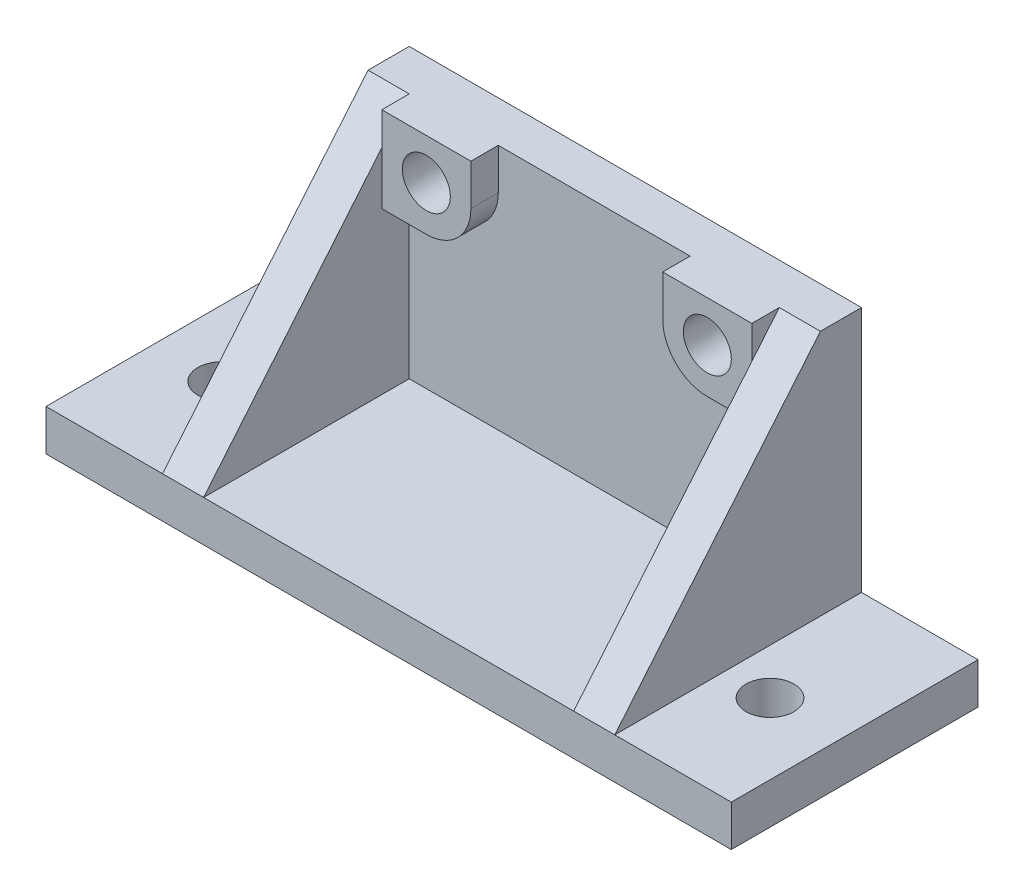
SolidWorks part; units mm, degrees
ref_plane "Alzado" through (0, 0, 0) normal (0, 0, 1) x (1, 0, 0)
ref_plane "Planta" through (0, 0, 0) normal (0, 1, 0) x (1, 0, 0)
ref_plane "Vista lateral" through (0, 0, 0) normal (1, 0, 0) x (0, 0, -1)
sketch "Croquis1" plane through (0, 0, 0) normal (0, 0, 1) x (1, 0, 0)
  point P0 (0, 0)
  point P8 (16.5, 0)
  line B0 (0, 0) -> (33, 0)
  line B1 (0, 0) -> (0, -21)
  line B2 (0, -21) -> (33, -21)
  line B3 (33, 0) -> (33, -21)
  circle B4 centre (6.25, -3) radius 1.75
  circle B5 centre (26.75, -3) radius 1.75
sketch_block_instance "Bloque1-1"
sketch_block "Bloque1"
extrude "Saliente-Extruir1" add sketch "Croquis1" along normal blind 3
sketch "Croquis2" plane through (0, 0, 3) normal (0, 0, 1) x (1, 0, 0)
  line L0 (0, 0) -> (0, -21)
  line L1 (0, -21) -> (33, -21)
  line L2 (33, -21) -> (33, 0)
  line L3 (33, 0) -> (30, 0)
  line L4 (33, 0) -> (0, 0) construction
  line L5 (30, 0) -> (30, -18)
  line L6 (30, -18) -> (3, -18)
  line L7 (3, -18) -> (3, 0)
  line L8 (3, 0) -> (0, 0)
  dimension "D1" = 3
  dimension "D2" = 3
  dimension "D3" = 3
extrude "Saliente-Extruir2" add sketch "Croquis2" along normal blind 15
sketch "Croquis3" plane through (0, 0, 0) normal (-1, 0, 0) x (0, 0, 1)
  line L0 (3, 0) -> (18, -18)
  line L1 (18, 0) -> (0, 0) construction
  line L2 (18, 0) -> (18, -21) construction
  line L3 (18, -18) -> (18, 0)
  line L4 (18, 0) -> (3, 0)
  line L5 (18, -21) -> (0, -21) construction
  dimension "D1" = 3
  dimension "D2" = 3
extrude "Cortar-Extruir1" cut sketch "Croquis3" against normal through all
sketch "Croquis4" plane through (0, -18, 0) normal (0, 1, 0) x (1, 0, 0)
  line L0 (30, -18) -> (3, -18) construction
  line L1 (0, -18) -> (-8.5, -18)
  line L2 (0, -18) -> (0, 0)
  line L3 (0, 0) -> (-8.5, 0)
  line L4 (-8.5, -18) -> (-8.5, 0)
  line L5 (33, 0) -> (41.5, 0)
  line L6 (33, 0) -> (33, -18)
  line L7 (33, -18) -> (41.5, -18)
  line L8 (41.5, 0) -> (41.5, -18)
  line L10 (33, 0) -> (0, 0) construction
  line L11 (33, -3) -> (33, -18) construction
  point P14 (55.1891, 0)
  dimension "D1" = 8.5
  dimension "D2" = 8.5
extrude "Saliente-Extruir3" add sketch "Croquis4" against normal up to surface (3 mm away) up to face at (16.5, -21, 9)
sketch "Croquis5" plane through (0, 0, 3) normal (0, 0, 1) x (1, 0, 0)
  line L0 (3, -18) -> (3, 0) construction
  line L1 (6.25, -6.25) -> (3, -6.25)
  line L2 (3, -6.25) -> (3, 0)
  line L3 (3, 0) -> (9.5, 0)
  line L4 (30, 0) -> (3, 0) construction
  line L5 (9.5, 0) -> (9.5, -3)
  line L6 (16.5, 0) -> (16.5, -18) construction
  line L7 (30, -18) -> (3, -18) construction
  line L8 (23.5, 0) -> (23.5, -3)
  line L9 (30, 0) -> (23.5, 0)
  line L10 (30, -6.25) -> (30, 0)
  line L11 (26.75, -6.25) -> (30, -6.25)
  arc A0 (6.25, -6.25) -> (9.5, -3) centre (6.25, -3) ccw
  arc A2 (26.75, -6.25) -> (23.5, -3) centre (26.75, -3) cw
  circle A3 centre (26.75, -3) radius 1.75 construction
  circle A4 centre (6.25, -3) radius 1.75 construction
  circle A5 centre (26.75, -3) radius 1.75
  circle A6 centre (6.25, -3) radius 1.75
extrude "Saliente-Extruir4" add sketch "Croquis5" along normal blind 2
sketch "Croquis6" plane through (33, 0, 0) normal (1, 0, 0) x (0, 0, -1)
  line L3 (-5, 0) -> (-5, -2.4)
  line L4 (-5, -2.4) -> (-3, 0)
  line L5 (-3, 0) -> (-5, 0)
  line L6 (-5, 0) -> (-5, -2.4)
  line L7 (-5, -2.4) -> (-3, 0)
  line L8 (-3, 0) -> (-5, 0)
  dimension "D1" = 0
sketch "Croquis8" plane through (0, -21, 0) normal (0, -1, 0) x (1, 0, 0)
  circle A0 centre (-3.675, 10) radius 1.75 construction
  circle A1 centre (36.325, 10) radius 1.75 construction
  circle A2 centre (-3.675, 10) radius 1.75
  circle A3 centre (36.325, 10) radius 1.75
extrude "Cortar-Extruir4" cut sketch "Croquis8" against normal through all
